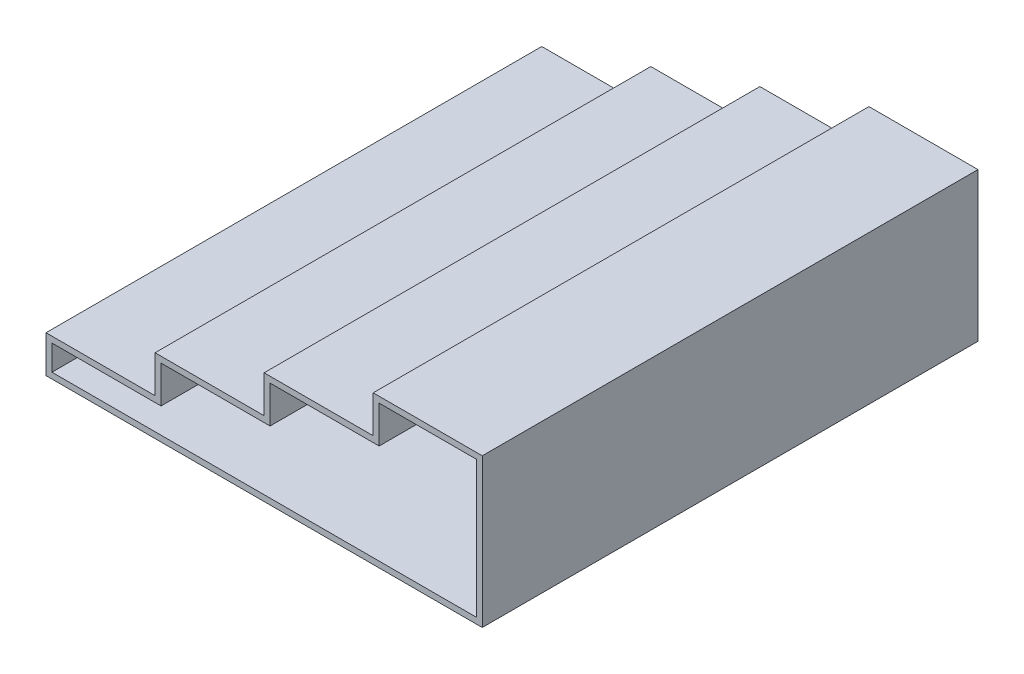
SolidWorks part; units mm, degrees
ref_plane "Front Plane" through (0, 0, 0) normal (0, 0, 1) x (1, 0, 0)
ref_plane "Top Plane" through (0, 0, 0) normal (0, 1, 0) x (1, 0, 0)
ref_plane "Right Plane" through (0, 0, 0) normal (1, 0, 0) x (0, 0, -1)
sketch "Sketch1" plane through (0, 0, 0) normal (0, 0, 1) x (1, 0, 0)
  line L0 (0, 0) -> (0, 18.75)
  line L1 (0, -55) -> (0, 55) construction
  line L2 (0, 18.75) -> (55, 18.75)
  line L3 (55, 18.75) -> (55, 37.5)
  line L4 (55, 37.5) -> (110, 37.5)
  line L5 (110, 37.5) -> (110, 56.25)
  line L6 (110, 56.25) -> (165, 56.25)
  line L7 (165, 56.25) -> (165, 75)
  line L8 (165, 75) -> (220, 75)
  line L13 (220, 0) -> (0, 0)
  line L14 (220, 75) -> (220, 0)
  dimension "D1" = 55
  dimension "D2" = 75
extrude "Boss-Extrude1" add sketch "Sketch1" along normal mid plane 250
shell "Shell1" thickness 3
